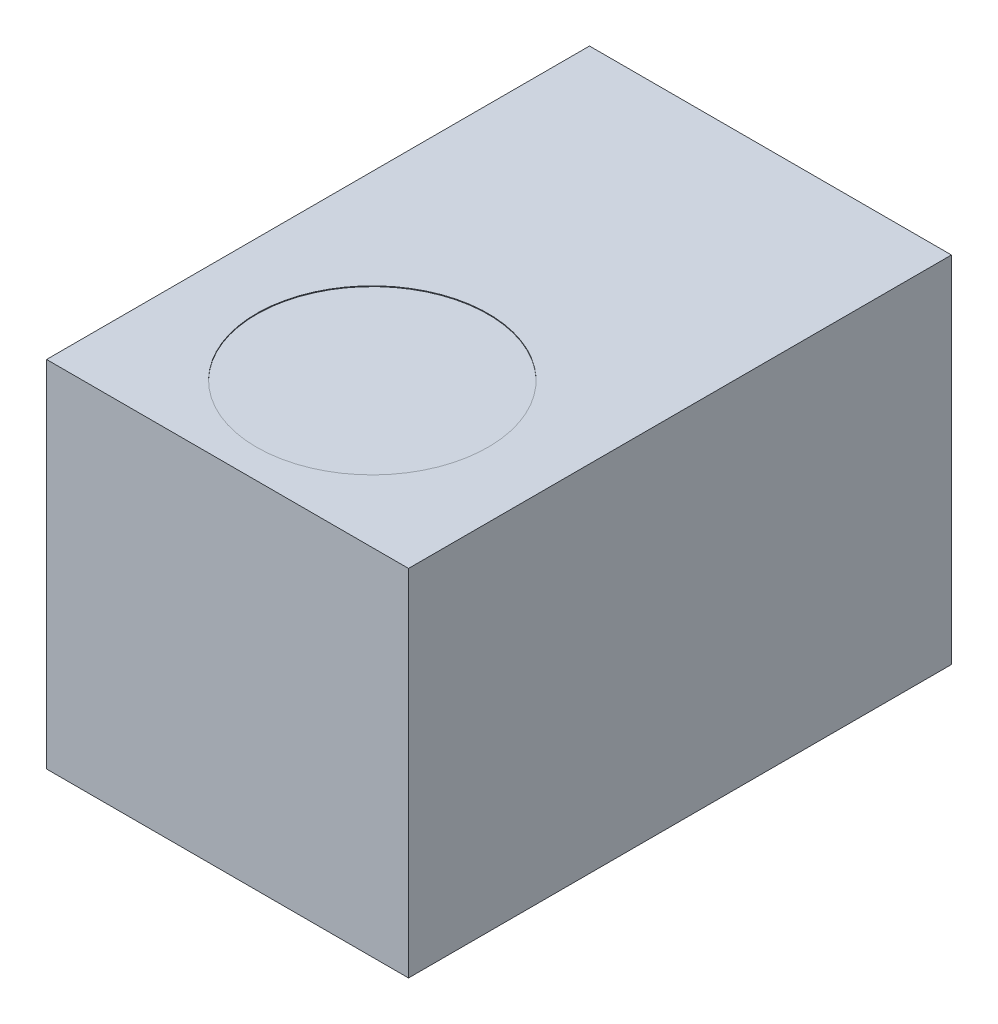
SolidWorks part; units mm, degrees
ref_plane "Front Plane" through (0, 0, 0) normal (0, 0, 1) x (1, 0, 0)
ref_plane "Top Plane" through (0, 0, 0) normal (0, 1, 0) x (1, 0, 0)
ref_plane "Right Plane" through (0, 0, 0) normal (1, 0, 0) x (0, 0, -1)
sketch "Sketch1" plane through (0, 0, 0) normal (1, 0, 0) x (0, 0, -1)
  line L1 (-37.5, 24.5) -> (37.5, 24.5)
  line L2 (-37.5, 24.5) -> (-37.5, -24.5)
  line L3 (-37.5, -24.5) -> (37.5, -24.5)
  line L4 (37.5, 24.5) -> (37.5, -24.5)
  line L5 (-37.5, 24.5) -> (37.5, -24.5) construction
  line L6 (-37.5, -24.5) -> (37.5, 24.5) construction
  point P0 (0, 0)
  dimension "D1" = 49
  dimension "D2" = 75
extrude "Boss-Extrude1" add sketch "Sketch1" along normal blind 50
sketch "Sketch2" plane through (0, -24.5, 0) normal (0, -1, 0) x (1, 0, 0)
  line L0 (50, 37.5) -> (0, 37.5) construction
  line L1 (5, 35.5) -> (45, 35.5)
  line L2 (5, 35.5) -> (5, -16.5)
  line L3 (5, -16.5) -> (45, -16.5)
  line L4 (45, 35.5) -> (45, -16.5)
  point P4 (25, 35.5)
  point P7 (25, 37.5)
  dimension "D1" = 40
  dimension "D2" = 52
  dimension "D3" = 2
extrude "Cut-Extrude1" cut sketch "Sketch2" against normal blind 40
sketch "Sketch3" plane through (0, 24.5, 0) normal (0, 1, 0) x (1, 0, 0)
  line L0 (50, 37.5) -> (0, 37.5) construction
  line L1 (50, -37.5) -> (0, -37.5) construction
  circle A0 centre (25, -17.5) radius 16
  point P2 (0, 0)
  point P5 (25, 37.5)
  point P6 (25, 16.3122)
  dimension "D1" = 32
  dimension "D2" = 20
extrude "Cut-Extrude3" cut sketch "Sketch3" against normal blind 0.1
